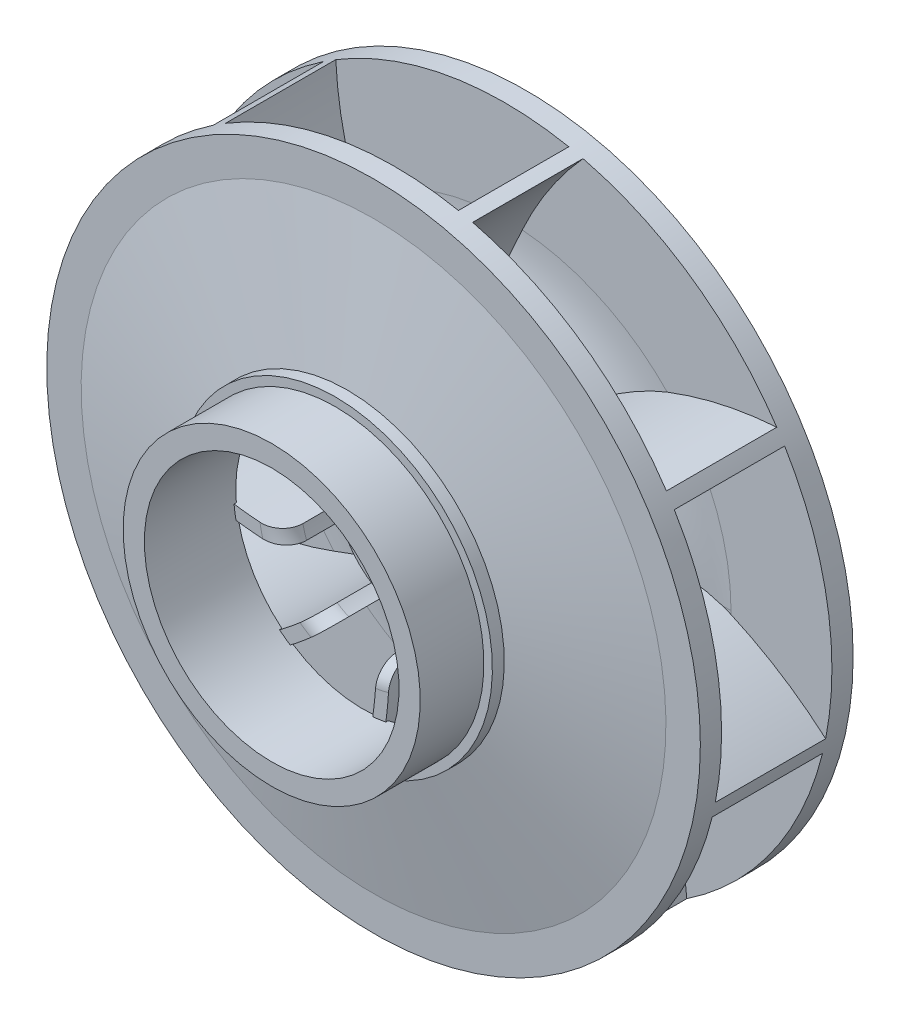
SolidWorks part; units mm, degrees
material "AISI 304"
ref_plane "Front Plane" through (0, 0, 0) normal (0, 0, 1) x (1, 0, 0)
ref_plane "Top Plane" through (0, 0, 0) normal (0, 1, 0) x (1, 0, 0)
ref_plane "Right Plane" through (0, 0, 0) normal (1, 0, 0) x (0, 0, -1)
sketch "Sketch1" plane through (0, 0, 0) normal (1, 0, 0) x (0, 0, -1)
  line L0 (0, 0) -> (50, 0) construction
  line L1 (0, 17.5) -> (0, 9)
  line L2 (0, 9) -> (32, 9)
  line L3 (32, 9) -> (32, 22)
  line L4 (32, 22) -> (27, 22)
  line L5 (27, 22) -> (27, 36)
  line L6 (27, 36) -> (32, 36)
  line L7 (32, 36) -> (32, 37.5)
  line L8 (32, 37.5) -> (47, 37.5)
  line L9 (47, 37.5) -> (47, 42.5)
  line L10 (47, 42.5) -> (27, 42.5)
  line L11 (27, 42.5) -> (27, 77)
  line L12 (27, 77) -> (22, 77)
  line L13 (22, 77) -> (22, 53.2211)
  arc A0 (22, 53.2211) -> (0, 17.5) centre (-18, 53.2211) cw
  dimension "D15" = 40
  dimension "D1" = 50
  dimension "D2" = 18
  dimension "D3" = 32
  dimension "D4" = 35
  dimension "D5" = 44
  dimension "D6" = 5
  dimension "D7" = 20
  dimension "D8" = 15
  dimension "D9" = 75
  dimension "D10" = 72
  dimension "D11" = 85
  dimension "D12" = 5
  dimension "D13" = 47
  dimension "D14" = 154
revolve "Revolve1" add sketch "Sketch1" angle 360 about L0
sketch "Sketch2" plane through (0, 0, -22) normal (0, 0, 1) x (1, 0, 0)
  arc A0 (64.0117, 42.796) -> (7.8513, 17.302) centre (70, -45) ccw
  arc A1 (65.8565, 39.8989) -> (10.5808, 15.7812) centre (70, -45) ccw
  circle A3 centre (0, 0) radius 77 construction
  arc A4 (-20.8799, -74.115) -> (-3.6985, -76.9111) centre (0, 0) ccw
  arc A5 (65.8565, 39.8989) -> (64.0117, 42.796) centre (0, 0) ccw
  arc A6 (10.5808, 15.7812) -> (7.8513, 17.302) centre (0, 0) ccw
  dimension "D1" = 88
  dimension "D2" = 85
  dimension "D5" = 19
  dimension "D3" = 70
  dimension "D4" = 45
extrude "Boss-Extrude1" add sketch "Sketch2" along normal blind 34 contours A0 A6 A1 A5
fillet "Fillet1" radius 5 1 edges at (9.2473, 16.5978, 12)
pattern_circular "CirPattern1" count 8 over 360 about axis through (0, 0, 0) along (0, 0, 1) of "Fillet1", "Boss-Extrude1"
sketch "Sketch3" plane through (0, 0, 0) normal (1, 0, 0) x (0, 0, -1)
  line L0 (0, 0) -> (-40, 0) construction
  line L1 (-33, 35) -> (-33, 30)
  line L2 (-33, 30) -> (-11.4671, 30)
  line L3 (-33, 35) -> (-18, 35)
  line L4 (-18, 35) -> (-18, 37)
  line L5 (-18, 37) -> (-15.2, 37)
  line L6 (-15.2, 37) -> (-9, 68.8962)
  line L7 (-9, 68.8962) -> (-9, 77)
  line L8 (-9, 77) -> (-4, 77)
  line L9 (-4, 77) -> (-4, 68.4148)
  line L10 (-4, 68.4148) -> (-11.4671, 30)
  line L11 (22, 77) -> (22, 65.8565) construction
  point P16 (0, 0)
  dimension "D1" = 40
  dimension "D2" = 60
  dimension "D3" = 70
  dimension "D4" = 33
  dimension "D5" = 15
  dimension "D6" = 2.8
  dimension "D7" = 74
  dimension "D8" = 26
  dimension "D9" = 5
  dimension "D10" = 11
  dimension "D11" = 5
  dimension "D12" = 154
revolve "Revolve2" add sketch "Sketch3" angle 360 about L0
sketch "Sketch4" plane through (0, 0, 0) normal (1, 0, 0) x (0, 0, -1)
  line L0 (-15.2, 37) -> (-15.2, 77.456)
  line L1 (-15.2, 77.456) -> (-9, 77.456)
  line L2 (-9, 77) -> (-9, 65.8565) construction
  line L3 (-9, 77.456) -> (-9, 68.8962)
  line L4 (-9, 68.8962) -> (-9, 56.815) construction
  line L5 (-9, 68.8962) -> (-15.2, 37)
  line L6 (-15.2, 37) -> (-15.2, -37) construction
  point P2 (0, 0)
  point P9 (-9, 71.6579)
  point P12 (-9, 71.204)
  point P13 (-9, 68.8085)
  point P14 (-9, 65.6504)
  point P15 (0, 0)
  point P17 (0, 0)
  point P18 (-15.2, 37)
revolve "Cut-Revolve1" cut sketch "Sketch4" angle 360 about L0
sketch "Sketch5" plane through (0, 0, 0) normal (0, 0, 1) x (1, 0, 0)
  line L1 (-3, 11.8) -> (3, 11.8)
  line L2 (-3, 11.8) -> (-3, 6.8)
  line L3 (-3, 6.8) -> (3, 6.8)
  line L4 (3, 11.8) -> (3, 6.8)
  point P5 (0, 6.8)
  dimension "D1" = 6
  dimension "D2" = 11.8
  dimension "D3" = 5
extrude "Cut-Extrude1" cut sketch "Sketch5" against normal up to next
